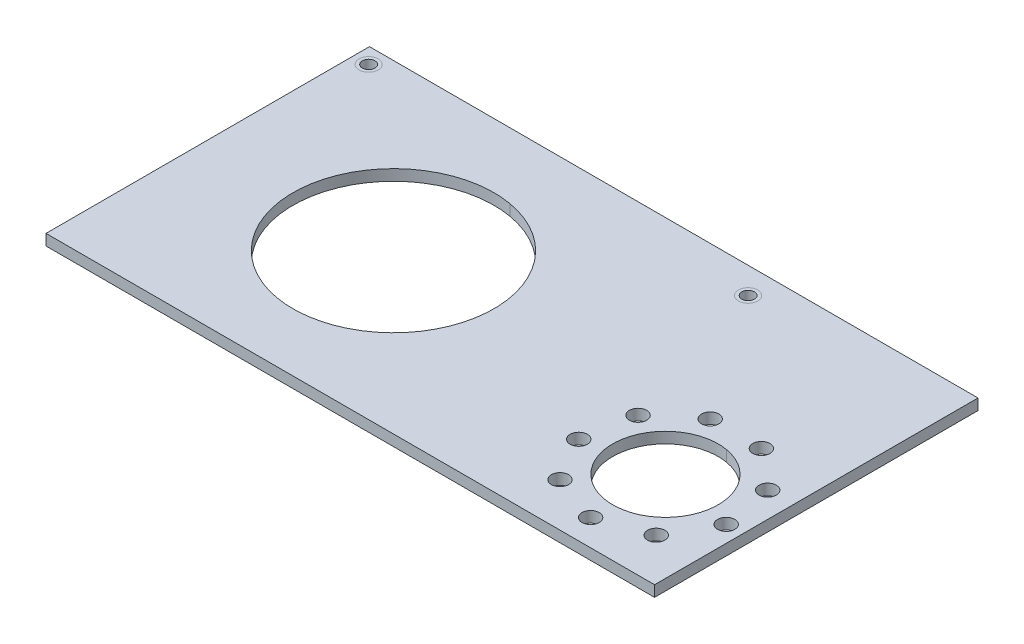
SolidWorks part; units mm, degrees
material "6061-T6 (SS)"
ref_plane "X-Y Datum" through (0, 0, 0) normal (0, 0, 1) x (1, 0, 0)
ref_plane "X-Z Datum" through (0, 0, 0) normal (0, 1, 0) x (1, 0, 0)
ref_plane "Y-Z Datum" through (0, 0, 0) normal (1, 0, 0) x (0, 0, -1)
sketch "Master Sketch" plane through (0, 0, 0) normal (0, 1, 0) x (1, 0, 0)
  line L11 (-752.0152, -13.883) -> (-764.7764, 4.3419) construction
  line L12 (-782.859, -11.9424) -> (-766.0654, -26.536) construction
  line L13 (-548.0506, -28.7869) -> (-538.648, -8.6228) construction
  line L14 (-561.7919, -1.105) -> (-566.0335, -22.9455) construction
  line L15 (-662.94, -95.25) -> (-669.29, -84.2515) construction
  line L16 (-662.94, 0) -> (-662.94, -95.25) construction
  line L17 (-777.24, -241.3) -> (-777.24, 0) construction
  line L18 (-777.24, 0) -> (-662.94, 0) construction
  line L19 (-662.94, 0) -> (-548.64, 0) construction
  line L20 (-548.64, 0) -> (0, 0) construction
  line L21 (-497.5185, 0) -> (-497.5185, -127) construction
  line L30 (-479.5835, -159.0518) -> (-474.3186, -164.3167) construction
  line L31 (-490.6797, -170.2207) -> (-490.6797, -163.648) construction
  line L32 (-504.3573, -163.648) -> (-504.3573, -170.2207) construction
  line L33 (-517.3573, -164.225) -> (-517.3573, -163.648) construction
  arc A10 (-766.0654, -26.536) -> (-752.0152, -13.883) centre (-759.8176, -19.3463) ccw construction
  arc A11 (-782.5855, -11.5202) -> (-765.2248, 4.114) centre (-777.24, 0) ccw construction
  arc A12 (-553.4437, -25.3906) -> (-559.9227, -24.1323) centre (-556.6832, -24.7614) ccw construction
  arc A13 (-559.9227, -24.1323) -> (-553.4437, -25.3906) centre (-556.6832, -24.7614) ccw construction
  arc A14 (-566.0335, -22.9455) -> (-548.0506, -28.7869) centre (-556.6832, -24.7614) ccw construction
  circle A15 centre (-548.64, 0) radius 12.7 construction
  circle A16 centre (-669.29, -96.9515) radius 61.9125 construction
  circle A17 centre (-669.29, -96.9515) radius 52.3875 construction
  circle A18 centre (-777.24, -241.3) radius 12.7 construction
  circle A19 centre (-777.24, 0) radius 12.7 construction
  arc A36 (-471.0608, -164.5979) -> (-521.206, -166.4019) centre (-497.5185, -127) ccw construction
  arc A37 (-474.3186, -164.3167) -> (-471.0608, -164.5979) centre (-472.5226, -162.5207) ccw construction
  arc A38 (-479.5835, -159.0518) -> (-490.6797, -163.648) centre (-484.1797, -163.648) ccw construction
  arc A39 (-492.9683, -172.7483) -> (-490.6797, -170.2207) centre (-493.2197, -170.2207) ccw construction
  arc A40 (-502.0687, -172.7483) -> (-492.9683, -172.7483) centre (-497.5185, -127) ccw construction
  arc A41 (-504.3573, -170.2207) -> (-502.0687, -172.7483) centre (-501.8173, -170.2207) ccw construction
  arc A42 (-504.3573, -163.648) -> (-517.3573, -163.648) centre (-510.8573, -163.648) ccw construction
  arc A43 (-521.206, -166.4019) -> (-517.3573, -164.225) centre (-519.8973, -164.225) ccw construction
  circle A46 centre (-497.5185, -166) radius 4.5 construction
  circle A47 centre (-472.4498, -156.8757) radius 4.5 construction
  circle A48 centre (-459.111, -133.7723) radius 4.5 construction
  circle A49 centre (-463.7435, -107.5) radius 4.5 construction
  circle A50 centre (-484.1797, -90.352) radius 4.5 construction
  circle A51 centre (-510.8573, -90.352) radius 4.5 construction
  circle A52 centre (-531.2935, -107.5) radius 4.5 construction
  circle A53 centre (-535.926, -133.7723) radius 4.5 construction
  circle A54 centre (-522.5872, -156.8757) radius 4.5 construction
  circle A55 centre (-497.5185, -127) radius 27.4955 construction
  circle A61 centre (-612.14, -96.9515) radius 2.5 construction
  circle A62 centre (-726.44, -96.9515) radius 2.5 construction
  circle A63 centre (-669.29, -39.8015) radius 2.5 construction
  arc A64 (-669.29, -151.6015) -> (-669.29, -156.6015) centre (-669.29, -154.1015) ccw construction
  arc A65 (-669.29, -156.6015) -> (-669.29, -151.6015) centre (-669.29, -154.1015) ccw construction
  dimension "D1" = 104.775
  dimension "D2" = 123.825
  dimension "D3" = 5
  dimension "D4" = 54.991
  dimension "D5" = 9
  dimension "D6" = 9.525
  dimension "D7" = 12.7
  dimension "D8" = 3.3
  dimension "D9" = 45.974
  dimension "D10" = 2.54
  dimension "D11" = 6.5
  dimension "D12" = 459.111
  dimension "D13" = 463.7435
  dimension "D14" = 471.0608
  dimension "D15" = 472.4498
  dimension "D16" = 472.5226
  dimension "D17" = 474.3186
  dimension "D18" = 479.5835
  dimension "D19" = 538.648
  dimension "D20" = 548.0506
  dimension "D21" = 548.64
  dimension "D22" = 556.6832
  dimension "D23" = 662.94
  dimension "D24" = 752.0152
  dimension "D25" = 759.8176
  dimension "D26" = 39.8015
  dimension "D27" = 84.2515
  dimension "D28" = 90.352
  dimension "D29" = 522.5872
  dimension "D30" = 531.2935
  dimension "D31" = 535.926
  dimension "D32" = 95.25
  dimension "D33" = 96.9515
  dimension "D34" = 107.5
  dimension "D35" = 553.4437
  dimension "D36" = 127
  dimension "D37" = 559.9227
  dimension "D38" = 133.7723
  dimension "D39" = 154.1015
  dimension "D40" = 612.14
  dimension "D41" = 156.8757
  dimension "D42" = 669.29
  dimension "D43" = 726.44
  dimension "D47" = 765.2248
  dimension "D50" = 782.5855
  dimension "D52" = 166
  dimension "D56" = 241.3
sketch "Sketch2" plane through (0, 0, 0) normal (0, 1, 0) x (1, 0, 0)
  line L0 (-479.5835, -159.0518) -> (-474.3186, -164.3167) construction
  line L1 (-490.6797, -170.2207) -> (-490.6797, -163.648) construction
  line L2 (-504.3573, -163.648) -> (-504.3573, -170.2207) construction
  line L3 (-497.5185, 0) -> (-497.5185, -127) construction
  line L4 (-548.0506, -28.7869) -> (-538.648, -8.6228) construction
  line L5 (-561.7919, -1.105) -> (-566.0335, -22.9455) construction
  line L6 (-548.64, 0) -> (0, 0) construction
  line L7 (-662.94, 0) -> (-548.64, 0) construction
  line L8 (-662.94, 0) -> (-662.94, -95.25) construction
  line L9 (-752.0152, -13.883) -> (-764.7764, 4.3419) construction
  line L10 (-782.859, -11.9424) -> (-766.0654, -26.536) construction
  line L11 (-777.24, 0) -> (-662.94, 0) construction
  line L12 (-777.24, -241.3) -> (-777.24, 0) construction
  line L13 (-479.5835, -159.0518) -> (-474.3186, -164.3167) construction
  line L14 (-490.6797, -170.2207) -> (-490.6797, -163.648) construction
  line L15 (-504.3573, -163.648) -> (-504.3573, -170.2207) construction
  line L16 (-497.5185, 0) -> (-497.5185, -127) construction
  line L17 (-548.0506, -28.7869) -> (-538.648, -8.6228) construction
  line L18 (-561.7919, -1.105) -> (-566.0335, -22.9455) construction
  line L19 (-548.64, 0) -> (0, 0) construction
  line L20 (-662.94, 0) -> (-548.64, 0) construction
  line L21 (-662.94, 0) -> (-662.94, -95.25) construction
  line L22 (-752.0152, -13.883) -> (-764.7764, 4.3419) construction
  line L23 (-782.859, -11.9424) -> (-766.0654, -26.536) construction
  line L24 (-777.24, 0) -> (-662.94, 0) construction
  line L25 (-777.24, -241.3) -> (-777.24, 0) construction
  line L31 (-669.29, -96.9515) -> (-497.5185, -127) construction
  line L32 (-767.6376, -11.1167) -> (-450.5427, -11.1167)
  line L33 (-767.6376, -11.1167) -> (-767.6376, -179.6528)
  line L34 (-767.6376, -179.6528) -> (-450.5427, -179.6528)
  line L35 (-450.5427, -11.1167) -> (-450.5427, -179.6528)
  circle A0 centre (-484.1797, -90.352) radius 4.5 construction
  circle A1 centre (-510.8573, -90.352) radius 4.5 construction
  circle A2 centre (-463.7435, -107.5) radius 4.5 construction
  circle A3 centre (-531.2935, -107.5) radius 4.5 construction
  circle A4 centre (-497.5185, -127) radius 27.4955 construction
  circle A5 centre (-459.111, -133.7723) radius 4.5 construction
  circle A6 centre (-535.926, -133.7723) radius 4.5 construction
  circle A7 centre (-472.4498, -156.8757) radius 4.5 construction
  circle A8 centre (-522.5872, -156.8757) radius 4.5 construction
  circle A9 centre (-497.5185, -166) radius 4.5 construction
  arc A10 (-479.5835, -159.0518) -> (-490.6797, -163.648) centre (-484.1797, -163.648) ccw construction
  arc A11 (-474.3186, -164.3167) -> (-471.0608, -164.5979) centre (-472.5226, -162.5207) ccw construction
  arc A12 (-492.9683, -172.7483) -> (-490.6797, -170.2207) centre (-493.2197, -170.2207) ccw construction
  arc A13 (-502.0687, -172.7483) -> (-492.9683, -172.7483) centre (-497.5185, -127) ccw construction
  arc A14 (-504.3573, -170.2207) -> (-502.0687, -172.7483) centre (-501.8173, -170.2207) ccw construction
  arc A15 (-504.3573, -163.648) -> (-517.3573, -163.648) centre (-510.8573, -163.648) ccw construction
  arc A16 (-471.0608, -164.5979) -> (-521.206, -166.4019) centre (-497.5185, -127) ccw construction
  arc A17 (-521.206, -166.4019) -> (-517.3573, -164.225) centre (-519.8973, -164.225) ccw construction
  arc A18 (-559.9227, -24.1323) -> (-553.4437, -25.3906) centre (-556.6832, -24.7614) ccw construction
  arc A19 (-553.4437, -25.3906) -> (-559.9227, -24.1323) centre (-556.6832, -24.7614) ccw construction
  arc A20 (-566.0335, -22.9455) -> (-548.0506, -28.7869) centre (-556.6832, -24.7614) ccw construction
  circle A21 centre (-548.64, 0) radius 12.7 construction
  circle A22 centre (-612.14, -96.9515) radius 2.5 construction
  arc A23 (-669.29, -151.6015) -> (-669.29, -156.6015) centre (-669.29, -154.1015) ccw construction
  arc A24 (-669.29, -156.6015) -> (-669.29, -151.6015) centre (-669.29, -154.1015) ccw construction
  circle A25 centre (-726.44, -96.9515) radius 2.5 construction
  circle A26 centre (-669.29, -96.9515) radius 52.3875 construction
  circle A27 centre (-669.29, -39.8015) radius 2.5 construction
  circle A28 centre (-669.29, -96.9515) radius 61.9125 construction
  arc A29 (-766.0654, -26.536) -> (-752.0152, -13.883) centre (-759.8176, -19.3463) ccw construction
  circle A30 centre (-777.24, 0) radius 12.7 construction
  circle A31 centre (-777.24, -241.3) radius 12.7 construction
  circle A32 centre (-484.1797, -90.352) radius 4.5
  circle A33 centre (-510.8573, -90.352) radius 4.5
  circle A34 centre (-463.7435, -107.5) radius 4.5
  circle A35 centre (-531.2935, -107.5) radius 4.5
  circle A36 centre (-497.5185, -127) radius 27.4955
  circle A37 centre (-459.111, -133.7723) radius 4.5
  circle A38 centre (-535.926, -133.7723) radius 4.5
  circle A39 centre (-472.4498, -156.8757) radius 4.5
  circle A40 centre (-522.5872, -156.8757) radius 4.5
  circle A41 centre (-497.5185, -166) radius 4.5
  arc A42 (-479.5835, -159.0518) -> (-490.6797, -163.648) centre (-484.1797, -163.648) ccw construction
  arc A43 (-474.3186, -164.3167) -> (-471.0608, -164.5979) centre (-472.5226, -162.5207) ccw construction
  arc A44 (-492.9683, -172.7483) -> (-490.6797, -170.2207) centre (-493.2197, -170.2207) ccw construction
  arc A45 (-502.0687, -172.7483) -> (-492.9683, -172.7483) centre (-497.5185, -127) ccw construction
  arc A46 (-504.3573, -170.2207) -> (-502.0687, -172.7483) centre (-501.8173, -170.2207) ccw construction
  arc A47 (-504.3573, -163.648) -> (-517.3573, -163.648) centre (-510.8573, -163.648) ccw construction
  arc A48 (-471.0608, -164.5979) -> (-521.206, -166.4019) centre (-497.5185, -127) ccw construction
  arc A49 (-521.206, -166.4019) -> (-517.3573, -164.225) centre (-519.8973, -164.225) ccw construction
  arc A50 (-559.9227, -24.1323) -> (-553.4437, -25.3906) centre (-556.6832, -24.7614) ccw
  arc A51 (-553.4437, -25.3906) -> (-559.9227, -24.1323) centre (-556.6832, -24.7614) ccw
  arc A52 (-566.0335, -22.9455) -> (-548.0506, -28.7869) centre (-556.6832, -24.7614) ccw construction
  circle A53 centre (-548.64, 0) radius 12.7 construction
  circle A54 centre (-612.14, -96.9515) radius 2.5 construction
  arc A55 (-669.29, -151.6015) -> (-669.29, -156.6015) centre (-669.29, -154.1015) ccw construction
  arc A56 (-669.29, -156.6015) -> (-669.29, -151.6015) centre (-669.29, -154.1015) ccw construction
  circle A57 centre (-726.44, -96.9515) radius 2.5 construction
  circle A58 centre (-669.29, -96.9515) radius 52.3875
  circle A59 centre (-669.29, -39.8015) radius 2.5 construction
  circle A60 centre (-669.29, -96.9515) radius 61.9125 construction
  arc A61 (-766.0654, -26.536) -> (-752.0152, -13.883) centre (-759.8176, -19.3463) ccw construction
  circle A62 centre (-777.24, 0) radius 12.7 construction
  circle A63 centre (-777.24, -241.3) radius 12.7 construction
  circle A64 centre (-759.8176, -19.3463) radius 3.3
  point P106 (-766.0654, -11.9424)
  point P107 (-768.6507, -11.9424)
  point P108 (-454.2848, -13.883)
  point P109 (-451.8554, -11.2341)
  point P110 (-450.9019, -11.1167)
  dimension "D1" = 7.82
  dimension "D2" = 317.0949
  dimension "D3" = 8.2296
  dimension "D4" = 168.5361
extrude "Boss-Extrude1" add sketch "Sketch2" along normal blind 5.715
ref_point "Point1"
ref_point "Point2"
ref_plane "Plane1" through (-669.29, 0, 96.9515) normal (0.985, 0, 0.1723) x (0.1723, 0, -0.985)
ref_plane "Plane2" through (-497.5185, 0, 127) normal (0.985, 0, 0.1723) x (0.1723, 0, -0.985)
split line "Split Line1"
split line "Split Line2"
sketch "Sketch3" plane through (0, 0, 0) normal (0, -1, 0) x (1, 0, 0)
  circle A0 centre (-759.8176, 19.3463) radius 5
  circle A1 centre (-556.6832, 24.7614) radius 5
  dimension "D1" = 10
  dimension "D2" = 10
sketch "Sketch4" plane through (0, 5.715, 0) normal (0, 1, 0) x (1, 0, 0)
  circle A0 centre (-556.6832, -24.7614) radius 5 construction
  circle A1 centre (-759.8176, -19.3463) radius 5 construction
  circle A2 centre (-556.6832, -24.7614) radius 5
  circle A3 centre (-759.8176, -19.3463) radius 5
split line "Split Line3"
split line "Split Line4"
sketch "Sketch5" plane through (0, 0, 0) normal (0, -1, 0) x (1, 0, 0)
  circle A0 centre (-669.29, 96.9515) radius 61.9125 construction
  circle A1 centre (-669.29, 96.9515) radius 61.9125
split line "Split Line5"
